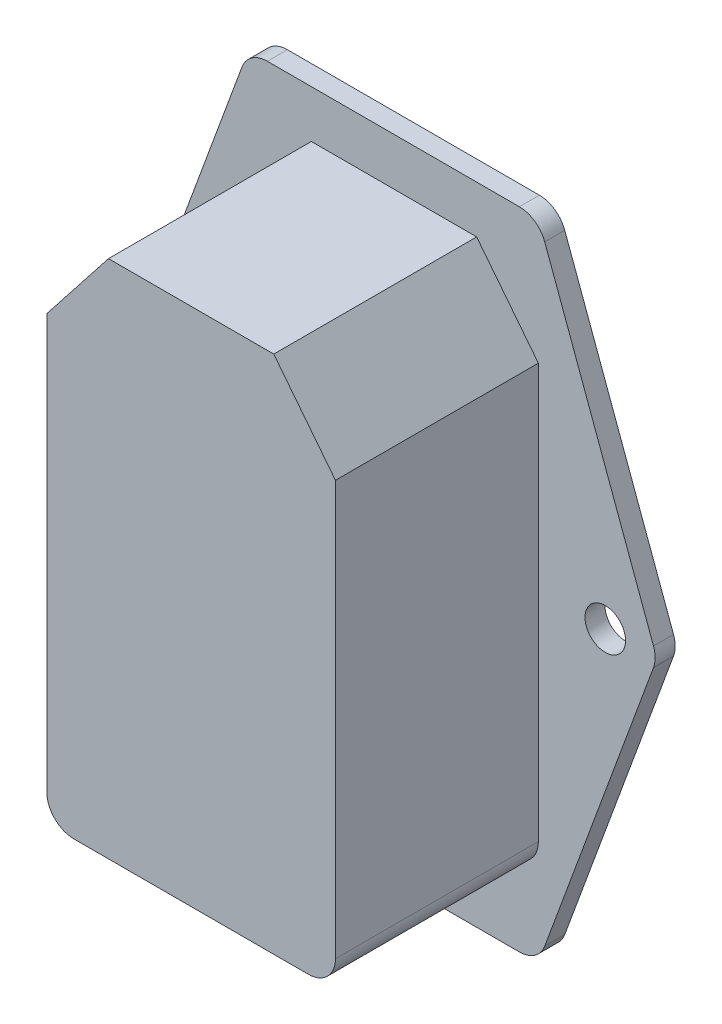
SolidWorks part; units mm, degrees
ref_plane "Front Plane" through (0, 0, 0) normal (0, 0, 1) x (1, 0, 0)
ref_plane "Top Plane" through (0, 0, 0) normal (0, 1, 0) x (1, 0, 0)
ref_plane "Right Plane" through (0, 0, 0) normal (1, 0, 0) x (0, 0, -1)
sketch "Sketch1" plane through (0, 0, 0) normal (0, 0, 1) x (1, 0, 0)
  line L0 (2.54, 0) -> (24.5618, 0)
  line L1 (27.1018, 2.54) -> (27.1018, 41.4401)
  line L2 (27.1018, 41.4401) -> (21.3106, 48.8095)
  line L3 (21.3106, 48.8095) -> (5.7912, 48.8095)
  line L4 (0, 2.54) -> (0, 41.4401)
  line L5 (0, 41.4401) -> (5.7912, 48.8095)
  arc A0 (2.54, 0) -> (0, 2.54) centre (2.54, 2.54) cw
  arc A1 (24.5618, 0) -> (27.1018, 2.54) centre (24.5618, 2.54) ccw
  point P10 (0, 0)
  point P13 (27.1018, 0)
  dimension "D5" = 2.54
  dimension "D7" = 2.54
  dimension "D1" = 27.1018
  dimension "D2" = 41.4401
  dimension "D3" = 9.3726
  dimension "D4" = 15.5194
  dimension "D6" = 9.3726
extrude "Boss-Extrude1" add sketch "Sketch1" along normal blind 19.05
sketch "Sketch2" plane through (0, 0, 0) normal (0, 0, 1) x (1, 0, 0)
  line L0 (1.6576, 53.2672) -> (25.3172, 53.2672)
  line L2 (27.1018, 2.54) -> (27.1018, 41.4401) construction
  line L3 (0, 41.4401) -> (0, 2.54) construction
  line L4 (21.3106, 48.8095) -> (5.7912, 48.8095) construction
  line L7 (27.701, 51.6043) -> (37.9145, 23.8468)
  line L8 (37.9145, 22.0925) -> (27.701, -5.665)
  line L9 (25.3172, -7.3279) -> (1.6576, -7.3279)
  line L10 (-0.7262, -5.665) -> (-10.9397, 22.0925)
  line L11 (-10.9397, 23.8468) -> (-0.7262, 51.6043)
  line L12 (2.54, 0) -> (24.5618, 0) construction
  arc A0 (1.6576, -7.3279) -> (-0.7262, -5.665) centre (1.6576, -4.7879) cw
  arc A1 (-10.9397, 22.0925) -> (-10.9397, 23.8468) centre (-8.556, 22.9696) cw
  arc A2 (27.701, -5.665) -> (25.3172, -7.3279) centre (25.3172, -4.7879) cw
  arc A3 (37.9145, 22.0925) -> (37.9145, 23.8468) centre (35.5308, 22.9696) ccw
  arc A4 (27.701, 51.6043) -> (25.3172, 53.2672) centre (25.3172, 50.7272) ccw
  arc A5 (-0.7262, 51.6043) -> (1.6576, 53.2672) centre (1.6576, 50.7272) cw
  point P10 (0, 0)
  point P16 (27.1018, 21.9901)
  point P21 (-11.2625, 22.9696)
  point P26 (38.2373, 22.9696)
  point P29 (27.0891, 53.2672)
  point P32 (-0.1143, 53.2672)
  dimension "D7" = 2.54
  dimension "D1" = 27.2034
  dimension "D2" = 4.4577
  dimension "D3" = 5.7785
  dimension "D4" = 7.3279
  dimension "D5" = 11.1355
  dimension "D6" = 11.2625
sketch "Sketch3" plane through (0, 0, 0) normal (0, 0, 1) x (1, 0, 0)
sketch "Sketch5" plane through (0, 0, 0) normal (0, 0, 1) x (1, 0, 0)
extrude "Boss-Extrude2" add sketch "Sketch2" against normal blind 1.8796
sketch "Sketch6" plane through (0, 0, 0) normal (0, 0, 1) x (1, 0, 0)
  line L0 (1.6576, -7.3279) -> (25.3172, -7.3279) construction
  circle A0 centre (33.3845, 22.9696) radius 1.905
  circle A1 centre (-6.4097, 22.9696) radius 1.905
  arc A3 (37.9145, 22.0925) -> (37.9145, 23.8468) centre (35.5308, 22.9696) ccw construction
  arc A4 (-10.9397, 23.8468) -> (-10.9397, 22.0925) centre (-8.556, 22.9696) ccw construction
  point P4 (0, 0)
  point P7 (0, 0)
  point P9 (38.0708, 22.9696)
  point P13 (-11.096, 22.9696)
  dimension "D1" = 3.81
  dimension "D2" = 4.6863
  dimension "D3" = 4.6863
  dimension "D4" = 30.2975
  dimension "D5" = 30.2975
extrude "Cut-Extrude1" cut sketch "Sketch6" against normal blind 20.4216 and the other way blind 22.606
